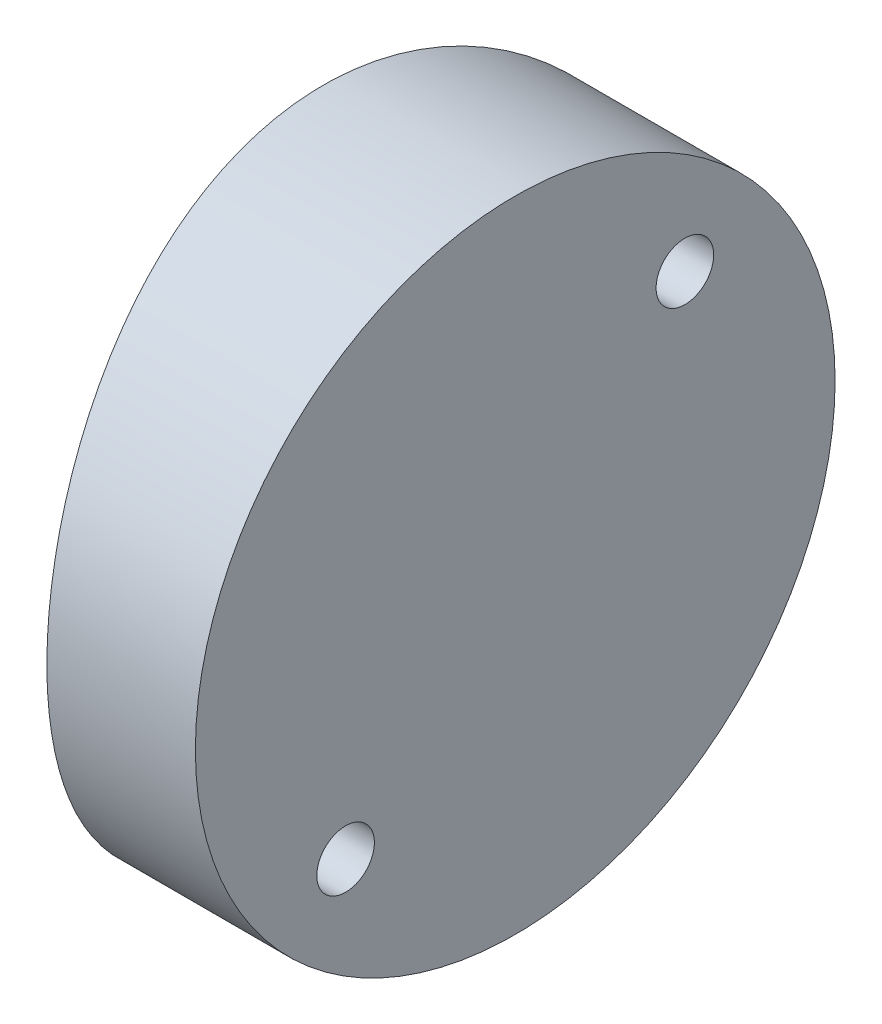
SolidWorks part; units mm, degrees
ref_plane "Plano frontal" through (0, 0, 0) normal (0, 0, 1) x (1, 0, 0)
ref_plane "Plano superior" through (0, 0, 0) normal (0, 1, 0) x (1, 0, 0)
ref_plane "Plano direito" through (0, 0, 0) normal (1, 0, 0) x (0, 0, -1)
sketch "Sketch1" plane through (0, 0, 0) normal (1, 0, 0) x (0, 0, -1)
  circle A0 centre (0, 0) radius 20
  dimension "D1" = 40
extrude "Bloco" add sketch "Sketch1" along normal blind 12
hole_wizard "Furo de Fixação - Parafuso M3" positions "Sketch5" profile "Sketch6" counterbore size "M3" standard "ANSI Metric" end condition up to next
sketch "Sketch5" plane through (0, 0, 0) normal (-1, 0, 0) x (0, 0, 1)
  line L1 (10.6066, -10.6066) -> (-10.6066, 10.6066) construction
  line L3 (20, 0) -> (-20, 0) construction
  circle A0 centre (0, 0) radius 20 construction
  point P12 (10.6066, -10.6066)
  point P22 (-10.6066, 10.6066)
  point P26 (0, 0)
  dimension "D1" = 45
  dimension "D2" = 15
sketch "Sketch6" plane through (0, -10.6066, 10.6066) normal (0, 1, 0) x (0, 0, 1)
  line L0 (0, 0) -> (0, 12)
  line L1 (0, 12) -> (1.8, 12)
  line L3 (1.8, 12) -> (1.8, 3)
  line L4 (1.8, 3) -> (3.25, 3)
  line L5 (3.25, 3) -> (3.25, 0)
  line L7 (3.25, 0) -> (0, 0)
  line L11 (0, -6.35) -> (0, 107.95) construction
  dimension "Thru Hole Dia." = 3.6
  dimension "Thru Hole Depth" = 12
  dimension "C'Bore Dia." = 6.5
  dimension "C'Bore Depth" = 3
sketch "Sketch7" plane through (0, 0, 0) normal (0, 1, 0) x (1, 0, 0)
  circle A0 centre (75, 0) radius 75
  circle A1 centre (75, 0) radius 75
  circle A2 centre (75, 0) radius 100
  dimension "D2" = 200
  dimension "D1" = 75
extrude "Corte - Arredondamento" cut sketch "Sketch7" against normal through all both and the other way through all contours A2 A0
